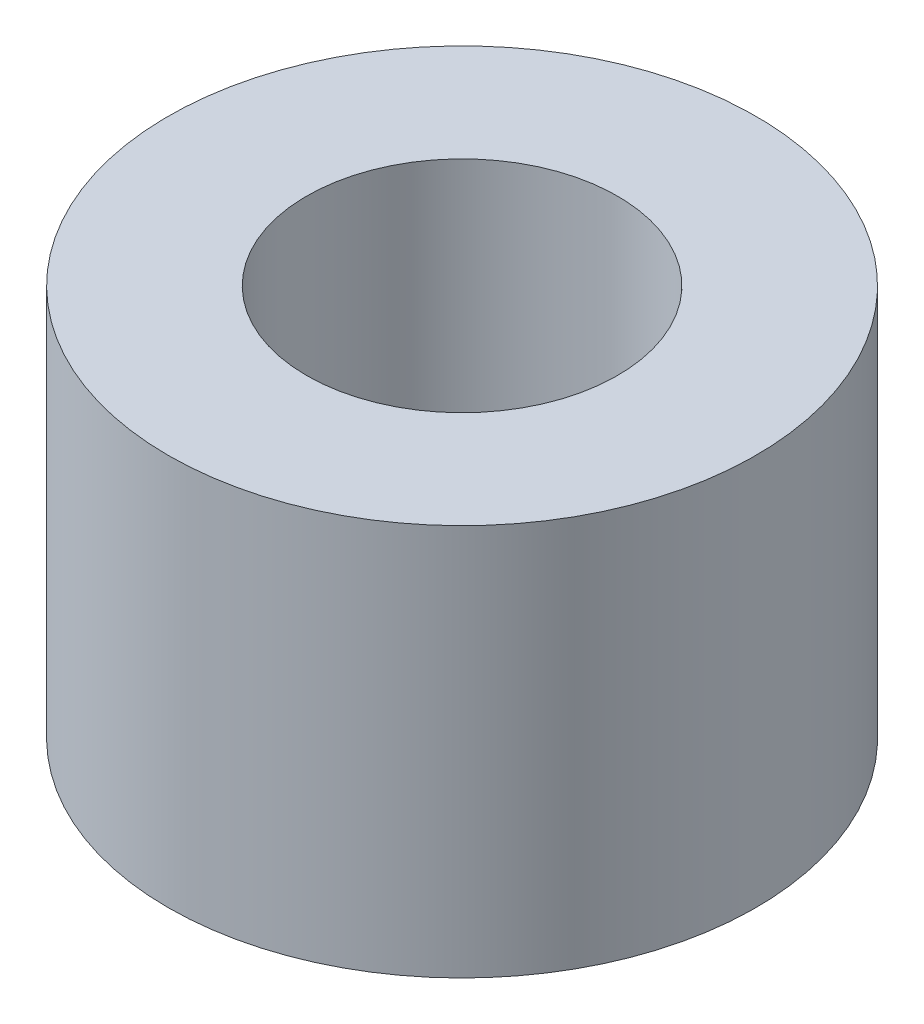
SolidWorks part; units mm, degrees
ref_plane "Front Plane" through (0, 0, 0) normal (0, 0, 1) x (1, 0, 0)
ref_plane "Top Plane" through (0, 0, 0) normal (0, 1, 0) x (1, 0, 0)
ref_plane "Right Plane" through (0, 0, 0) normal (1, 0, 0) x (0, 0, -1)
sketch "Sketch1" plane through (0, 0, 0) normal (0, 1, 0) x (1, 0, 0)
  circle A0 centre (0, 0) radius 9
  circle A1 centre (0, 0) radius 4.7625
  dimension "D1" = 18
  dimension "D2" = 9.525
extrude "Boss-Extrude1" add sketch "Sketch1" along normal blind 12
